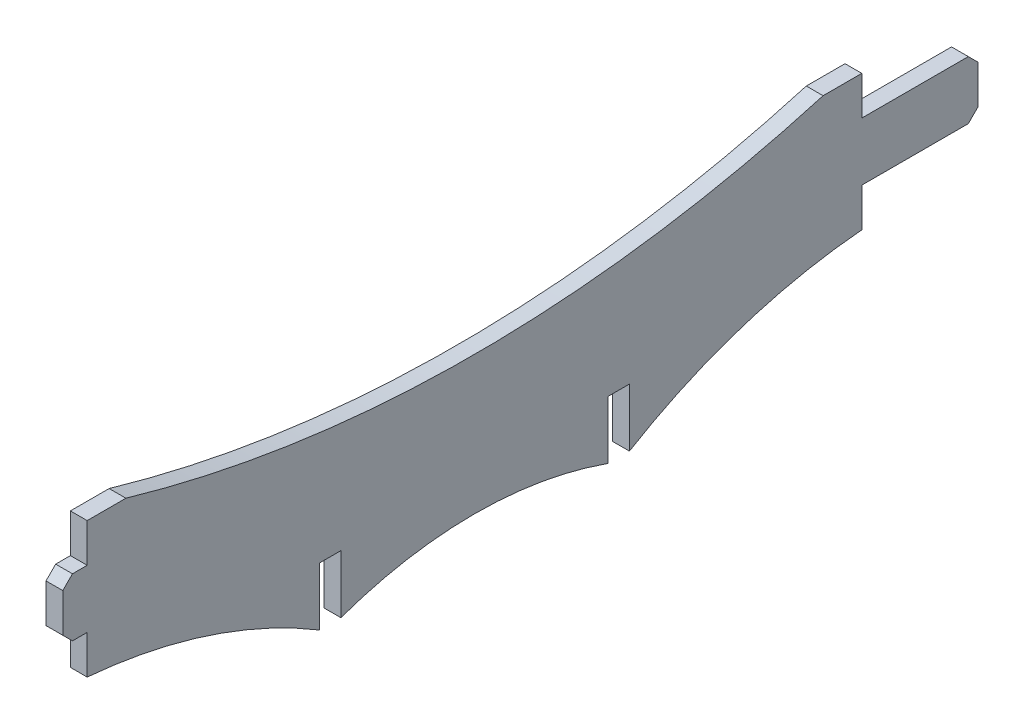
SolidWorks part; units mm, degrees
ref_plane "Front Plane" through (0, 0, 0) normal (1, 0, 0) x (0, 1, 0)
ref_plane "Top Plane" through (0, 0, 0) normal (0, 0, 1) x (0, 1, 0)
ref_plane "Right Plane" through (0, 0, 0) normal (0, 1, 0) x (-1, 0, 0)
sketch "Sketch1" plane through (0, 0, 0) normal (1, 0, 0) x (0, 1, 0)
  line L0 (-9.525, 19.05) -> (-15.875, 19.05)
  line L1 (0, 0) -> (-9.525, 0)
  line L2 (0, 0) -> (0, 19.05)
  line L4 (-9.525, 0) -> (-9.525, 19.05)
  line L5 (0, 19.05) -> (6.35, 19.05)
  line L6 (-18.7167, 57.15) -> (-18.7167, 60.65)
  line L7 (-18.7167, 57.15) -> (-28.2417, 57.15)
  line L8 (-18.7167, 60.65) -> (-28.2417, 60.65)
  line L9 (6.35, 146.05) -> (6.35, 139.7)
  line L10 (6.35, 19.05) -> (6.35, 25.4)
  line L13 (-18.7167, 107.95) -> (-28.2417, 107.95)
  line L14 (-18.7167, 104.45) -> (-28.2417, 104.45)
  line L15 (-18.7167, 107.95) -> (-18.7167, 104.45)
  line L16 (-15.875, 146.05) -> (-9.525, 146.05)
  line L17 (0, 146.05) -> (6.35, 146.05)
  line L19 (-9.525, 146.05) -> (-9.525, 150.05)
  line L20 (-9.525, 150.05) -> (0, 150.05)
  line L21 (0, 146.05) -> (0, 150.05)
  arc A0 (-15.875, 146.05) -> (-28.2417, 107.95) centre (-104.1343, 153.6406) cw
  arc A1 (-28.2417, 104.45) -> (-28.2417, 60.65) centre (-89.5005, 82.55) cw
  arc A2 (-15.875, 19.05) -> (-28.2417, 57.15) centre (-104.1343, 11.4594) ccw
  arc A3 (6.35, 139.7) -> (6.35, 25.4) centre (202.3857, 82.55) ccw
  point P27 (0, 0)
  point P28 (0, 0)
  point P29 (0, 0)
  point P30 (-28.2417, 95.25)
  point P31 (0, 0)
  dimension "D3" = 88.5851
  dimension "D6" = 38.1
  dimension "D11" = 12.3667
  dimension "D12" = 204.1963
  dimension "D14" = 65.0558
  dimension "D1" = 9.525
  dimension "D2" = 19.05
  dimension "D4" = 6.35
  dimension "D5" = 6.35
  dimension "D7" = 3.5
  dimension "D8" = 38.1
  dimension "D9" = 127
  dimension "D10" = 9.525
  dimension "D13" = 12.3667
  dimension "D15" = 4
extrude "Boss-Extrude1" add sketch "Sketch1" along normal blind 2.75
chamfer "Chamfer1" distance 1.5875 angle 45 4 edges at (1.375, 0, 0) (1.375, -9.525, 0) (1.375, 0, 150.05) (1.375, -9.525, 150.05)
equation "\"PlateThickness\" = 2.75mm"
equation "\"Kerf\"= 0.15mm"
equation "\"clearance\" = 0.005mm"
equation "\"SlotW\" = \"PlateThickness\" - \"Kerf\""
equation "\"D1@Boss-Extrude1\"=\"PlateThickness\""
